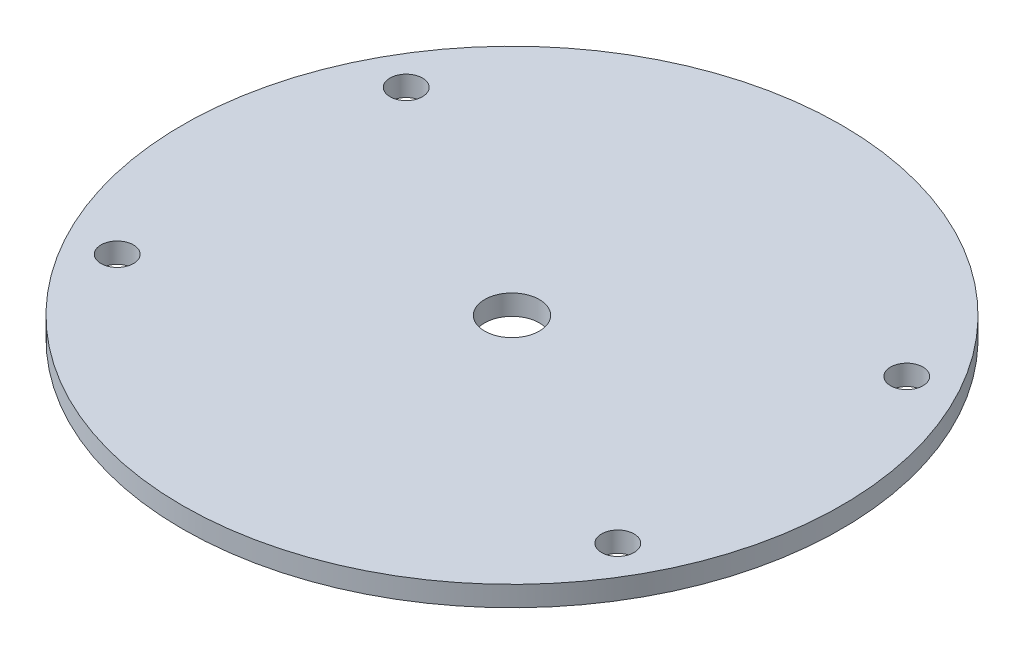
SolidWorks part; units mm, degrees
ref_plane "前视基准面" through (0, 0, 0) normal (0, 0, 1) x (1, 0, 0)
ref_plane "上视基准面" through (0, 0, 0) normal (0, 1, 0) x (1, 0, 0)
ref_plane "右视基准面" through (0, 0, 0) normal (1, 0, 0) x (0, 0, -1)
sketch "草图1" plane through (0, 0, 0) normal (0, 1, 0) x (1, 0, 0)
  line L0 (0, 0) -> (28.1458, -16.25) construction
  line L1 (0, 0) -> (32.5, 0) construction
  line L2 (0, 0) -> (0, -32.5) construction
  line L3 (-2.7, 4.2) -> (-2.7, -4.2) construction
  circle A0 centre (0, 0) radius 32.5
  circle A12 centre (24.6817, -14.25) radius 1.6
  circle A20 centre (-24.6817, -14.25) radius 1.6
  circle A21 centre (24.6817, 14.25) radius 1.6
  circle A22 centre (-24.6817, 14.25) radius 1.6
  circle A23 centre (0, 0) radius 2.7
  point P15 (0, 0)
  dimension "D1" = 30
  dimension "D2" = 65
  dimension "D6" = 3.2
  dimension "D7" = 4
extrude "凸台-拉伸1" add sketch "草图1" along normal blind 2
